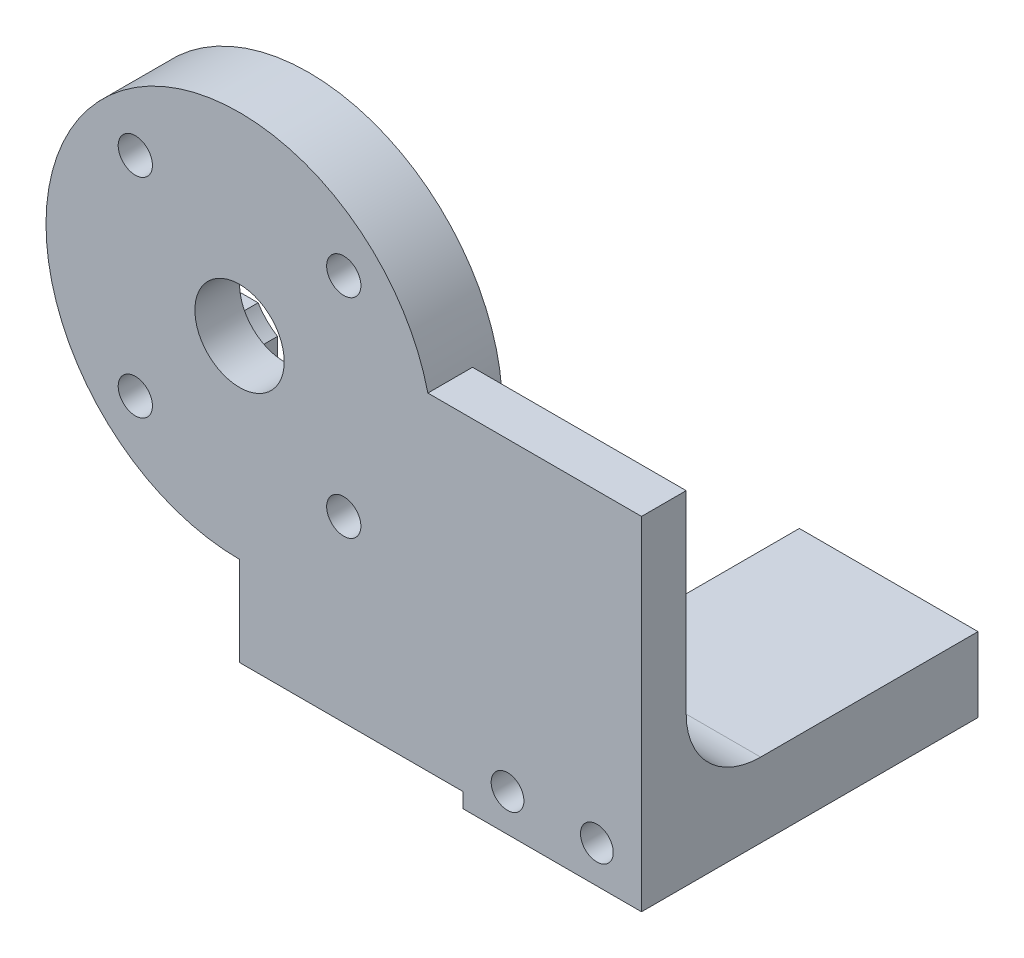
SolidWorks part; units mm, degrees
ref_plane "Front Plane" through (0, 0, 0) normal (0, 0, 1) x (1, 0, 0)
ref_plane "Top Plane" through (0, 0, 0) normal (0, 1, 0) x (1, 0, 0)
ref_plane "Right Plane" through (0, 0, 0) normal (1, 0, 0) x (0, 0, -1)
sketch "Stock_horn_attachment_profile" plane through (0, 0, 0) normal (0, 0, 1) x (1, 0, 0)
  circle A0 centre (0, 0) radius 13
  dimension "D1" = 26
extrude "Stock_horn_attachment" add sketch "Stock_horn_attachment_profile" along normal blind 3 from offset 19.6
sketch "Finger_arm_profile" plane through (0, 0, 0) normal (0, 0, 1) x (1, 0, 0)
  line L1 (0, -19) -> (27, -19)
  line L2 (0, -19) -> (0, 3)
  line L3 (0, 3) -> (27, 3)
  line L4 (27, -19) -> (27, 3)
  dimension "D1" = 27
  dimension "D2" = 22
  dimension "D3" = 3
extrude "Finger_arm" add sketch "Finger_arm_profile" along normal blind 3 from offset 19.6
sketch "Descending_contact_finger_profile" plane through (0, 0, 0) normal (0, 0, 1) x (1, 0, 0)
  line L1 (15, -20) -> (27, -20)
  line L2 (15, -20) -> (15, -15)
  line L3 (15, -15) -> (27, -15)
  line L4 (27, -20) -> (27, -15)
  dimension "D1" = 12
  dimension "D2" = 5
  dimension "D3" = 15
  dimension "D4" = 15
extrude "Descending_contact_finger" add sketch "Descending_contact_finger_profile" along normal blind 22.6
sketch "Horn_center_access_profile" plane through (0, 0, 0) normal (0, 0, 1) x (1, 0, 0)
  circle A0 centre (0, 0) radius 3
  dimension "D1" = 6
extrude "Horn_center_access" cut sketch "Horn_center_access_profile" along normal through all from offset 50
sketch "Captured_horn_key_boss_profile" plane through (0, 0, 0) normal (0, 0, 1) x (1, 0, 0)
  circle A0 centre (0, 0) radius 13
  dimension "D1" = 26
extrude "Captured_horn_key_boss" add sketch "Captured_horn_key_boss_profile" along normal blind 1.65 from offset 17.95
sketch "Stock_horn_pocket_Hub" plane through (0, 0, 0) normal (0, 0, 1) x (1, 0, 0)
  circle A0 centre (0, 0) radius 3.55
  dimension "D1" = 7.1
extrude "Key_pocket_Hub" cut sketch "Stock_horn_pocket_Hub" along normal blind 1.65 from offset 17.95
sketch "Stock_horn_pocket_Horizontal" plane through (0, 0, 0) normal (0, 0, 1) x (1, 0, 0)
  line L1 (-8.15, -2.1) -> (8.15, -2.1)
  line L2 (-8.15, -2.1) -> (-8.15, 2.1)
  line L3 (-8.15, 2.1) -> (8.15, 2.1)
  line L4 (8.15, -2.1) -> (8.15, 2.1)
  dimension "D1" = 16.3
  dimension "D2" = 4.2
  dimension "D3" = 8.15
  dimension "D4" = 2.1
extrude "Key_pocket_Horizontal" cut sketch "Stock_horn_pocket_Horizontal" along normal blind 1.65 from offset 17.95
sketch "Stock_horn_pocket_Vertical" plane through (0, 0, 0) normal (0, 0, 1) x (1, 0, 0)
  line L1 (-2.1, -8.15) -> (2.1, -8.15)
  line L2 (-2.1, -8.15) -> (-2.1, 8.15)
  line L3 (-2.1, 8.15) -> (2.1, 8.15)
  line L4 (2.1, -8.15) -> (2.1, 8.15)
  dimension "D1" = 4.2
  dimension "D2" = 16.3
  dimension "D3" = 2.1
  dimension "D4" = 8.15
extrude "Key_pocket_Vertical" cut sketch "Stock_horn_pocket_Vertical" along normal blind 1.65 from offset 17.95
sketch "Stock_horn_pocket_Rounded_tips" plane through (0, 0, 0) normal (0, 0, 1) x (1, 0, 0)
  circle A0 centre (8.15, 0) radius 2.1
  circle A1 centre (-8.15, 0) radius 2.1
  circle A2 centre (0, 8.15) radius 2.1
  circle A3 centre (0, -8.15) radius 2.1
  dimension "D1" = 4.2
  dimension "D2" = 4.2
  dimension "D3" = 4.2
  dimension "D4" = 4.2
  dimension "D5" = 8.15
  dimension "D6" = 8.15
  dimension "D7" = 8.15
  dimension "D8" = 8.15
extrude "Key_pocket_Rounded_tips" cut sketch "Stock_horn_pocket_Rounded_tips" along normal blind 1.65 from offset 17.95
sketch "Unmodified_horn_capture_M2_profile" plane through (0, 0, 0) normal (0, 0, 1) x (1, 0, 0)
  circle A0 centre (7, 7) radius 1.15
  circle A1 centre (-7, 7) radius 1.15
  circle A2 centre (-7, -7) radius 1.15
  circle A3 centre (7, -7) radius 1.15
  dimension "D1" = 2.3
  dimension "D2" = 2.3
  dimension "D3" = 2.3
  dimension "D4" = 2.3
  dimension "D5" = 7
  dimension "D6" = 7
  dimension "D7" = 7
  dimension "D8" = 7
extrude "Unmodified_horn_capture_M2" cut sketch "Unmodified_horn_capture_M2_profile" along normal through all from offset 50
sketch "Horn_center_hub_clearance" plane through (0, 0, 0) normal (0, 0, 1) x (1, 0, 0)
  circle A0 centre (0, 0) radius 4
  dimension "D1" = 8
extrude "Hub_clearance_in_key_boss_only" cut sketch "Horn_center_hub_clearance" along normal blind 1.65 from offset 17.95
sketch "Contact_pad_keeper_profile" plane through (0, 0, 0) normal (0, 0, 1) x (1, 0, 0)
  circle A0 centre (18, -17.5) radius 1.1
  circle A1 centre (24, -17.5) radius 1.1
  dimension "D1" = 2.2
  dimension "D2" = 2.2
  dimension "D3" = 18
  dimension "D4" = 24
  dimension "D5" = 17.5
extrude "Contact_pad_keeper" cut sketch "Contact_pad_keeper_profile" along normal through all from offset 50
fillet "Fillet1" radius 5 1 edges at (21, -15, 19.6)
